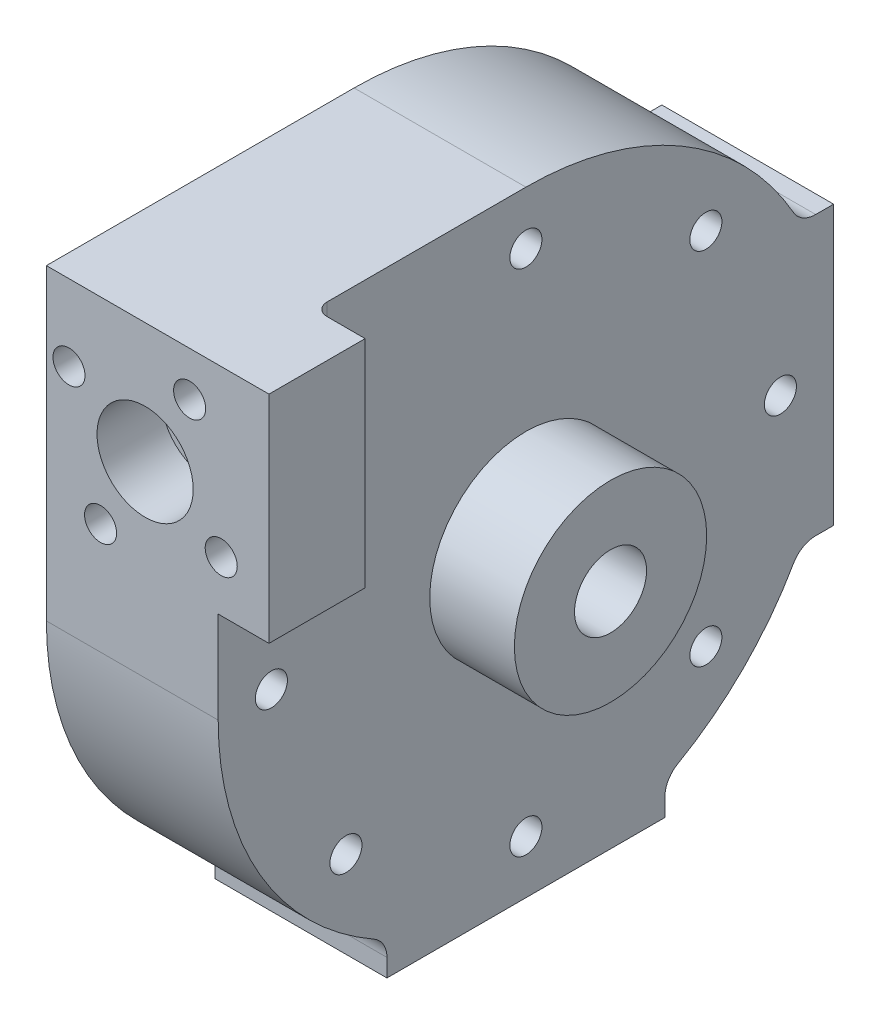
SolidWorks part; units mm, degrees
material "6061 Alloy"
ref_plane "Front Plane" through (0, 0, 0) normal (0, 0, 1) x (1, 0, 0)
ref_plane "Top Plane" through (0, 0, 0) normal (0, 1, 0) x (1, 0, 0)
ref_plane "Right Plane" through (0, 0, 0) normal (1, 0, 0) x (0, 0, -1)
sketch "Sketch1" plane through (0, 0, 0) normal (1, 0, 0) x (0, 0, -1)
  line L0 (-60.96, 0) -> (-60.96, 60.96)
  line L1 (-60.96, 60.96) -> (0, 60.96)
  line L2 (-27.53, -60.96) -> (27.53, -60.96)
  line L3 (27.53, -60.96) -> (27.53, -54.3895)
  line L4 (0, 55) -> (0, -55) construction
  line L5 (-27.53, -60.96) -> (-27.53, -54.3895)
  line L6 (60.96, 27.559) -> (60.96, -27.559)
  line L7 (60.96, -27.559) -> (54.3748, -27.559)
  line L8 (55, 0) -> (-55, 0) construction
  line L9 (60.96, 27.559) -> (54.3748, 27.559)
  arc A1 (-60.96, 0) -> (-27.53, -54.3895) centre (0, 0) ccw
  arc A2 (27.53, -54.3895) -> (54.3748, -27.559) centre (0, 0) ccw
  arc A3 (54.3748, 27.559) -> (0, 60.96) centre (0, 0) ccw
  point P17 (60.96, 0)
extrude "Housing 2" add sketch "Sketch1" along normal blind 44.45 contours L0 L1 A3 L9 L6 L7 A2 L3 L2 L5 A1
sketch "Sketch2" plane through (0, 0, 0) normal (-1, 0, 0) x (0, 0, 1)
  circle A0 centre (0, 0) radius 43.815
extrude "Impeller Cut" cut sketch "Sketch2" against normal blind 22.4028
sketch "Sketch3" plane through (0, 0, 0) normal (0, 0, 1) x (1, 0, 0)
  line L2 (29.6028, 9.6415) -> (22.4028, 43.815)
  line L3 (29.6028, 9.6415) -> (29.6028, 0)
  line L4 (44.45, 0) -> (0, 0) construction
  line L7 (22.4028, 43.815) -> (22.225, 0)
  line L8 (22.225, 0) -> (29.6028, 0)
revolve "Impeller Angle Cut" cut sketch "Sketch3" angle 360 about L8
sketch "Sketch4" plane through (29.6028, 0, 0) normal (-1, 0, 0) x (0, 0, 1)
  circle A0 centre (0, 0) radius 4.826
extrude "Inlet Cut" cut sketch "Sketch4" against normal blind 19.8628
sketch "Sketch5" plane through (44.45, 0, 0) normal (1, 0, 0) x (0, 0, -1)
  circle A1 centre (0, 19.05) radius 1.5875
extrude "Inlet Fastener Bore" [suppressed] cut sketch "Sketch5" against normal blind 6.35
pattern_circular "Inlet Fastener Pattern" [suppressed] count 6 over 360
sketch "Sketch6" plane through (44.45, 0, 0) normal (1, 0, 0) x (0, 0, -1)
  circle A2 centre (50.419, 0) radius 3.175
extrude "Fastener Bore" cut sketch "Sketch6" against normal blind 116.84
pattern_circular "Fastener Pattern" count 8 over 360 about axis through (0, 0, 0) along (1, 0, 0) skipping 5 of "Fastener Bore"
sketch "Sketch7" plane through (44.45, 0, 0) normal (1, 0, 0) x (0, 0, -1)
  circle A0 centre (0, 0) radius 19.05
  circle A1 centre (0, 0) radius 100.1143
extrude "Mass Reduction Cut" cut sketch "Sketch7" against normal blind 10.414
fillet "Fillet3" [suppressed] radius 5.08
sketch "Sketch8" plane through (0, 0, 60.96) normal (0, 0, 1) x (1, 0, 0)
  line L0 (34.036, 0) -> (34.036, 60.96) construction
  line L1 (0, 60.96) -> (34.036, 60.96)
  line L2 (0, 60.96) -> (0, 10.1635)
  line L3 (0, 10.1635) -> (34.036, 10.1635)
  line L4 (34.036, 60.96) -> (34.036, 10.1635)
extrude "Discharge Cut" [suppressed] cut sketch "Sketch8" against normal blind 2.54
fillet "Fillet4" [suppressed] radius 5.08
sketch "Sketch9" [suppressed] plane through (0, 0, 58.42) normal (0, 0, 1) x (1, 0, 0)
  circle A0 centre (19.6343, 36.5011) radius 2.54
extrude "Discharge Bore" [suppressed] cut sketch "Sketch9" against normal blind 50.038
sketch "Sketch11" plane through (44.45, 0, 0) normal (1, 0, 0) x (0, 0, -1)
  circle A0 centre (0, 0) radius 19.05
  circle A1 centre (0, 0) radius 4.826
extrude "Boss-Extrude1" add sketch "Sketch11" along normal blind 6.35
sketch "Sketch12" [suppressed] plane through (56.896, 0, 0) normal (1, 0, 0) x (0, 0, -1)
  circle A0 centre (19.976, 0) radius 3.175
extrude "Cut-Extrude1" [suppressed] cut sketch "Sketch12" against normal blind 19.05
pattern_circular "CirPattern1" [suppressed] count 6 over 360
fillet "Fillet6" [suppressed] radius 2.54
sketch "Sketch13" [suppressed] plane through (0, 0, 58.42) normal (0, 0, 1) x (1, 0, 0)
  circle A0 centre (19.6343, 36.5011) radius 9.525
extrude "Cut-Extrude2" [suppressed] cut sketch "Sketch13" against normal blind 25.4
sketch "Sketch14" plane through (0, 0, 0) normal (0, 0, 1) x (1, 0, 0)
  circle A0 centre (19.558, 37.084) radius 2.3813
extrude "Cut-Extrude3" cut sketch "Sketch14" along normal blind 99.06
sketch "Sketch15" plane through (0, 0, 60.96) normal (0, 0, 1) x (1, 0, 0)
  circle A0 centre (19.558, 37.084) radius 9.525
extrude "Cut-Extrude4" cut sketch "Sketch15" against normal blind 25.4
sketch "Sketch16" plane through (0, 0, 35.56) normal (0, 0, 1) x (1, 0, 0)
  circle A0 centre (19.558, 37.084) radius 9.525
  circle A1 centre (19.558, 37.084) radius 6.35
extrude "Boss-Extrude2" add sketch "Sketch16" along normal blind 12.7
sketch "Sketch18" plane through (0, 0, 60.96) normal (0, 0, 1) x (1, 0, 0)
  line L1 (34.036, 60.96) -> (44.0965, 60.96)
  line L2 (34.036, 60.96) -> (34.036, 18.1962)
  line L3 (34.036, 18.1962) -> (44.0965, 18.1962)
  line L4 (44.0965, 60.96) -> (44.0965, 18.1962)
extrude "Boss-Extrude3" add sketch "Sketch18" against normal blind 19.05
fillet "Fillet7" radius 2.54 1 edges at (34.036, 39.5781, 41.91)
sketch "Sketch19" plane through (0, 0, 60.96) normal (0, 0, 1) x (1, 0, 0)
  circle A1 centre (34.6406, 28.2636) radius 3.175
extrude "Cut-Extrude5" cut sketch "Sketch19" against normal blind 15.24
fillet "Fillet8" [suppressed] radius 2.54
ref_plane "Plane1" [suppressed] through (34.036, -60.96, 27.53) normal (0, 0, -1) x (-1, 0, 0)
ref_plane "Plane2" [suppressed] through (34.036, -60.96, -27.53) normal (0, 0, -1) x (-1, 0, 0)
fillet "Fillet9" radius 5.08 4 edges at (17.018, -27.559, -54.3748) (17.018, 27.559, -54.3748) (17.018, -54.3895, -27.53) (17.018, -54.3895, 27.53)
sketch "Sketch20" plane through (0, 60.96, 0) normal (0, 1, 0) x (1, 0, 0)
  circle A0 centre (19.8775, -40.3269) radius 0.6493
extrude "Cut-Extrude6" [suppressed] cut sketch "Sketch20" against normal blind 51.562
sketch "Sketch21" [suppressed] plane through (0, 60.96, 0) normal (0, 1, 0) x (1, 0, 0)
  circle A0 centre (19.8775, -40.3269) radius 4.7625
extrude "Cut-Extrude7" [suppressed] cut sketch "Sketch21" against normal blind 6.35
sketch "Sketch22" plane through (50.8, 0, 0) normal (1, 0, 0) x (0, 0, -1)
  circle A0 centre (0, 0) radius 7.1374
extrude "Cut-Extrude8" cut sketch "Sketch22" against normal blind 17.78
pattern_circular "CirPattern2" count 4 over 360 about axis through (19.558, 37.084, 0) along (0, 0, 1) of "Cut-Extrude5"
